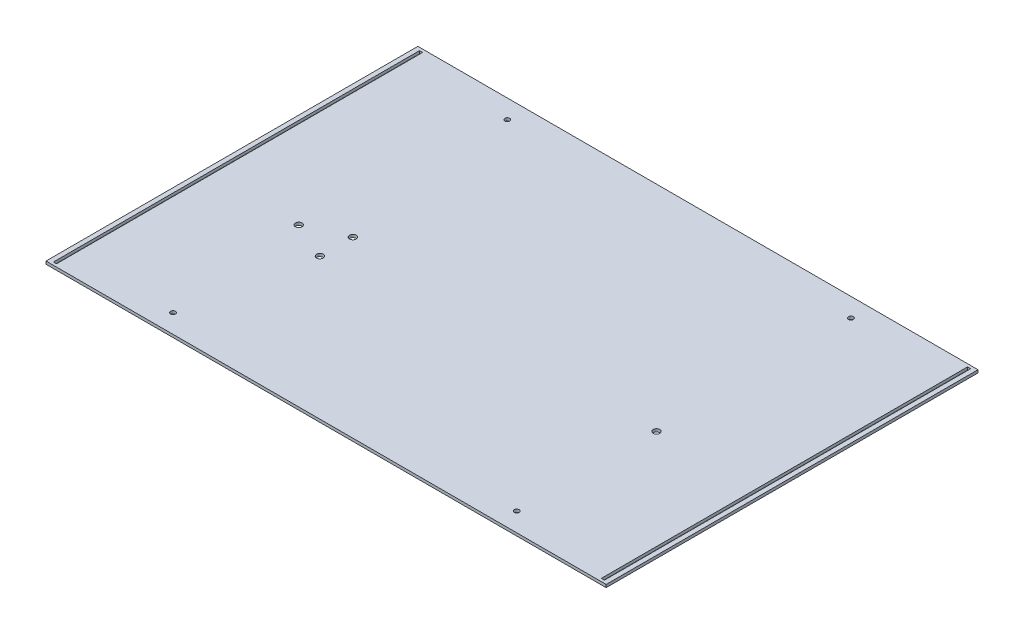
SolidWorks part; units mm, degrees
ref_plane "Front Plane" through (0, 0, 0) normal (0, 0, 1) x (1, 0, 0)
ref_plane "Top Plane" through (0, 0, 0) normal (0, 1, 0) x (1, 0, 0)
ref_plane "Right Plane" through (0, 0, 0) normal (1, 0, 0) x (0, 0, -1)
sketch "Sketch1" plane through (0, 0, 0) normal (0, 1, 0) x (1, 0, 0)
  line L1 (-297.5, 197.5) -> (297.5, 197.5)
  line L2 (-297.5, 197.5) -> (-297.5, -197.5)
  line L3 (-297.5, -197.5) -> (297.5, -197.5)
  line L4 (297.5, 197.5) -> (297.5, -197.5)
  line L5 (-297.5, 197.5) -> (297.5, -197.5) construction
  line L6 (-297.5, -197.5) -> (297.5, 197.5) construction
  point P0 (0, 0)
  dimension "D1" = 595
  dimension "D2" = 395
extrude "Boss-Extrude1" add sketch "Sketch1" along normal blind 3
sketch "Sketch2" plane through (0, 3, 0) normal (0, 1, 0) x (1, 0, 0)
  circle A0 centre (-196.5, -30) radius 3.55
  circle A1 centre (-156.5, -47.5) radius 3.55
  circle A2 centre (-156.5, -12.5) radius 3.55
  circle A3 centre (183.5, -30) radius 3.55
  dimension "D1" = 7.1
extrude "Cut-Extrude1" cut sketch "Sketch2" against normal through all both and the other way through all
sketch "Sketch3" plane through (0, 3, 0) normal (0, 1, 0) x (1, 0, 0)
  line L1 (292.65, -194.5) -> (289.35, -194.5)
  line L2 (292.65, -194.5) -> (292.65, 194.5)
  line L3 (292.65, 194.5) -> (289.35, 194.5)
  line L4 (289.35, -194.5) -> (289.35, 194.5)
  line L5 (292.65, -194.5) -> (289.35, 194.5) construction
  line L6 (292.65, 194.5) -> (289.35, -194.5) construction
  line L7 (-292.65, -194.5) -> (-289.35, -194.5)
  line L8 (-292.65, -194.5) -> (-292.65, 194.5)
  line L9 (-292.65, 194.5) -> (-289.35, 194.5)
  line L10 (-289.35, -194.5) -> (-289.35, 194.5)
  line L11 (-292.65, -194.5) -> (-289.35, 194.5) construction
  line L12 (-292.65, 194.5) -> (-289.35, -194.5) construction
  line L13 (-297.5, 197.5) -> (-297.5, -197.5) construction
  point P0 (291, 0)
  point P6 (-291, 0)
  point P11 (-289.35, 0)
  dimension "D1" = 3.3
  dimension "D2" = 389
  dimension "D3" = 3.3
  dimension "D4" = 389
  dimension "D5" = 4.85
extrude "Cut-Extrude2" cut sketch "Sketch3" against normal through all both and the other way through all
sketch "Sketch4" plane through (0, 0, 0) normal (0, -1, 0) x (-1, 0, 0)
  circle A0 centre (-182.5, -177.5) radius 2.6
  circle A1 centre (182.5, -177.5) radius 2.6
  circle A2 centre (182.5, 177.5) radius 2.6
  circle A3 centre (-182.5, 177.5) radius 2.6
  point P12 (0, 0)
  point P13 (0, 0)
  point P14 (0, 0)
  point P15 (0, 0)
extrude "Cut-Extrude3" cut sketch "Sketch4" against normal through all both and the other way through all
